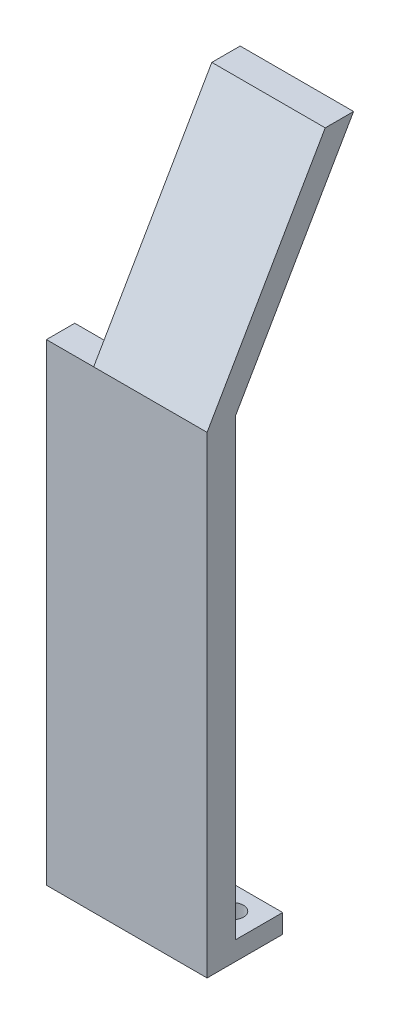
SolidWorks part; units mm, degrees
ref_plane "前视基准面" through (0, 0, 0) normal (0, 0, 1) x (1, 0, 0)
ref_plane "上视基准面" through (0, 0, 0) normal (0, 1, 0) x (1, 0, 0)
ref_plane "右视基准面" through (0, 0, 0) normal (1, 0, 0) x (0, 0, -1)
sketch "草图1" plane through (0, 0, 0) normal (0, 1, 0) x (1, 0, 0)
  line L0 (0, 0) -> (0, -1.2103) construction
  line L1 (-8.5, -2.5) -> (8.5, -2.5)
  line L2 (-8.5, -2.5) -> (-8.5, 2.5)
  line L3 (-8.5, 2.5) -> (8.5, 2.5)
  line L4 (8.5, -2.5) -> (8.5, 2.5)
  line L5 (-8.5, -2.5) -> (8.5, 2.5) construction
  line L6 (-8.5, 2.5) -> (8.5, -2.5) construction
  circle A0 centre (5.75, 0) radius 1.1
  circle A1 centre (-5.75, 0) radius 1.1
  circle A2 centre (0, 0) radius 1.1
  point P0 (0, 0)
  dimension "D2" = 5.75
  dimension "D1" = 17
  dimension "D3" = 5
extrude "凸台-拉伸1" add sketch "草图1" along normal blind 2
sketch "草图2" plane through (0, 0, 0) normal (0, 1, 0) x (1, 0, 0)
  line L0 (-8.5, -2.5) -> (-8.5, -5.5)
  line L1 (8.5, -2.5) -> (8.5, -5.5)
  line L2 (8.5, -5.5) -> (-8.5, -5.5)
  line L3 (-8.5, -2.5) -> (8.5, -2.5)
  dimension "D1" = 3
extrude "凸台-拉伸2" add sketch "草图2" along normal blind 50
sketch "草图3" plane through (8.5, 0, 0) normal (1, 0, 0) x (0, 0, -1)
  line L0 (-5.5, 50) -> (7, 71.6506)
  line L1 (-5.5, 50) -> (-5.5, 0) construction
  line L2 (7, 71.6506) -> (10, 71.6506)
  line L3 (-2.5, 50) -> (10, 71.6506)
  line L4 (-5.5, 50) -> (-2.5, 50)
  dimension "D1" = 30
  dimension "D2" = 3
  dimension "D3" = 25
extrude "凸台-拉伸3" add sketch "草图3" against normal blind 12
